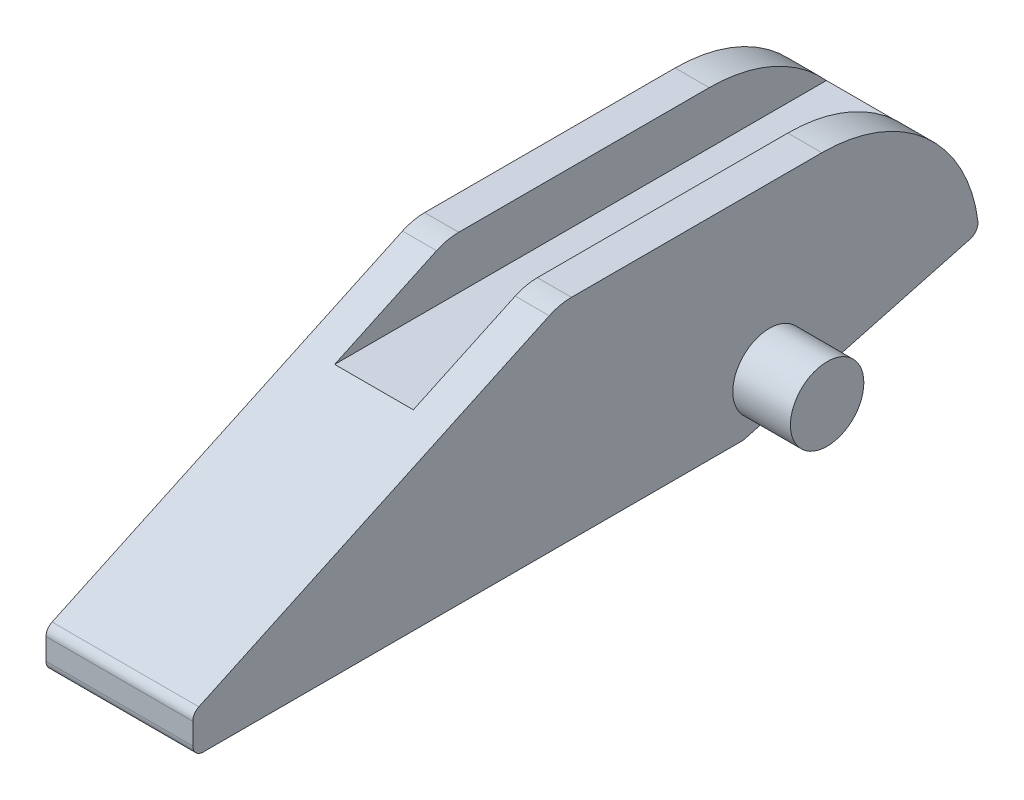
SolidWorks part; units mm, degrees
material "PC High Viscosity"
ref_plane "Front Plane" through (0, 0, 0) normal (0, 0, 1) x (1, 0, 0)
ref_plane "Top Plane" through (0, 0, 0) normal (0, 1, 0) x (1, 0, 0)
ref_plane "Right Plane" through (0, 0, 0) normal (1, 0, 0) x (0, 0, -1)
sketch "ProfileS" plane through (0, 0, 0) normal (1, 0, 0) x (0, 0, -1)
  line L12 (0, 0) -> (-15, 0)
  line L17 (93, 118) -> (527, 118) construction
  line L24 (-14.8845, 0.7893) -> (-8.2, 3.9063)
  line L25 (-7.7774, 4) -> (-3, 4)
  line L26 (0, 1) -> (0, 0)
  line L27 (-15, 0.608) -> (-15, 0)
  arc A15 (-3, 4) -> (0, 1) centre (-3, 1) cw
  arc A16 (-15, 0.608) -> (-14.8845, 0.7893) centre (-14.8, 0.608) cw
  arc A18 (-8.2, 3.9063) -> (-7.7774, 4) centre (-7.7774, 3) cw
  dimension "D1" = 3
  dimension "D6" = 1
  dimension "D7" = 8.2
  dimension "D5" = 15
  dimension "D2" = 25
  dimension "D3" = 0.2
  dimension "D4" = 4
extrude "Profile" add sketch "ProfileS" along normal mid plane 2.8
sketch "PivotTabS" plane through (0, 0, 0) normal (1, 0, 0) x (0, 0, -1)
  line L3 (-15, 0) -> (0, 0) construction
  circle A0 centre (-4, 0.9) radius 0.7
  dimension "D1" = 1.4
  dimension "D2" = 4
  dimension "D3" = 0.9
extrude "PivotTab" add sketch "PivotTabS" along normal mid plane 5
sketch "TopCutS" plane through (0, 4, 18.5121) normal (0, -1, 0) x (1, 0, 0)
  line L0 (0, -18.5121) -> (0, -3.5121) construction
  line L1 (-0.75, -3.5121) -> (0.75, -3.5121)
  line L2 (-0.75, -3.5121) -> (-0.75, -18.5121)
  line L3 (-0.75, -18.5121) -> (0.75, -18.5121)
  line L4 (0.75, -3.5121) -> (0.75, -18.5121)
  line L6 (1.4, -18.5121) -> (-1.4, -18.5121) construction
  line L8 (1.4, -3.5121) -> (-1.4, -3.5121) construction
  dimension "D1" = 1.5
extrude "TopCut" cut sketch "TopCutS" along normal blind 1
sketch "PivotSlantS" plane through (0, 0, 0) normal (1, 0, 0) x (0, 0, -1)
  line L0 (-4.5, 0) -> (0, 1.2058)
  line L1 (0, 1.2058) -> (0, 0)
  line L2 (0, 0) -> (-4.5, 0)
  line L3 (-15, 0) -> (0, 0) construction
  dimension "D1" = 15
  dimension "D2" = 4.5
extrude "PivotSlant" cut sketch "PivotSlantS" against normal through all both and the other way through all
fillet "PivotSlantF" radius 0.2 3 edges at (0, 1.2039, 0.0069) (0, 0, 4.5) (0, 0, 15)
sketch "BottomCavityS" plane through (0, 0, 0) normal (0, -1, 0) x (-1, 0, 0)
  line L0 (1.4, -9.6632) -> (-1.4, -9.6632) construction
  line L1 (-0.8, -13.8) -> (0.8, -13.8)
  line L2 (-0.8, -13.8) -> (-0.8, -5.5263)
  line L3 (-0.8, -5.5263) -> (0.8, -5.5263)
  line L4 (0.8, -13.8) -> (0.8, -5.5263)
  line L5 (-0.8, -13.8) -> (0.8, -5.5263) construction
  line L6 (-0.8, -5.5263) -> (0.8, -13.8) construction
  line L7 (1.4, -14.8) -> (1.4, -4.5263) construction
  line L8 (-1.4, -14.8) -> (-1.4, -4.5263) construction
  line L10 (1.4, -4.5263) -> (-1.4, -4.5263) construction
  point P0 (0, -9.6632)
  dimension "D1" = 0.6
  dimension "D2" = 1
extrude "BottomCavity" cut sketch "BottomCavityS" against normal blind 1
fillet "BottomCavityF" radius 0.2 8 edges at (0, 1, 13.8) (0.8, 1, 9.6632) (0, 1, 5.5263) (-0.8, 1, 9.6632) (-0.8, 0.5, 13.8) (-0.8, 0.5, 5.5263) (0.8, 0.5, 5.5263) (0.8, 0.5, 13.8)
